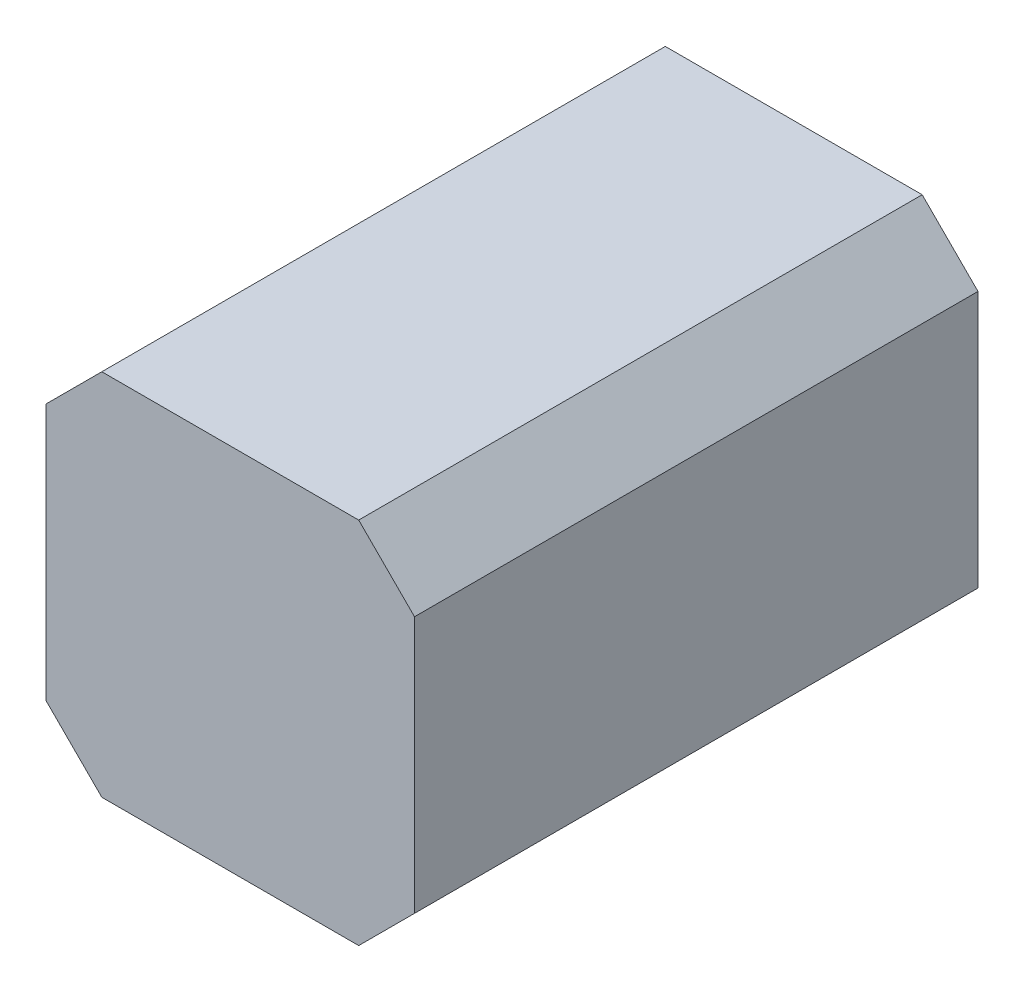
SolidWorks part; units mm, degrees
ref_plane "前视基准面" through (0, 0, 0) normal (0, 0, 1) x (1, 0, 0)
ref_plane "上视基准面" through (0, 0, 0) normal (0, 1, 0) x (1, 0, 0)
ref_plane "右视基准面" through (0, 0, 0) normal (1, 0, 0) x (0, 0, -1)
sketch "草图3" plane through (0, 0, 0) normal (0, 0, 1) x (1, 0, 0)
  line L0 (-77.5, -77.5) -> (77.5, 77.5) construction
  line L1 (-77.5, -77.5) -> (77.5, -77.5)
  line L2 (-77.5, -77.5) -> (-77.5, 77.5)
  line L3 (-77.5, 77.5) -> (77.5, 77.5)
  line L4 (77.5, -77.5) -> (77.5, 77.5)
  line L5 (54.0219, 77.5) -> (77.5, 54.0219)
  line L6 (77.5, -54.0219) -> (54.0219, -77.5)
  line L7 (-77.5, 77.5) -> (77.5, -77.5) construction
  line L8 (-77.5, 54.0219) -> (-54.0219, 77.5)
  line L9 (-54.0219, -77.5) -> (-77.5, -54.0219)
  point P0 (0, 0)
  point P15 (0, 0)
  dimension "D1" = 155
  dimension "D2" = 155
  dimension "D3" = 93
  dimension "D4" = 4
extrude "凸台-拉伸2" add sketch "草图3" along normal blind 237 contours L9 L1 L6 L4 L5 L3 L8 L2
ref_plane "基准面1" through (0, 0, 220) normal (0, 0, -1) x (-1, 0, 0)
scale "缩放比例1" scale about origin uniform scaling yes scale factor 0.76129
